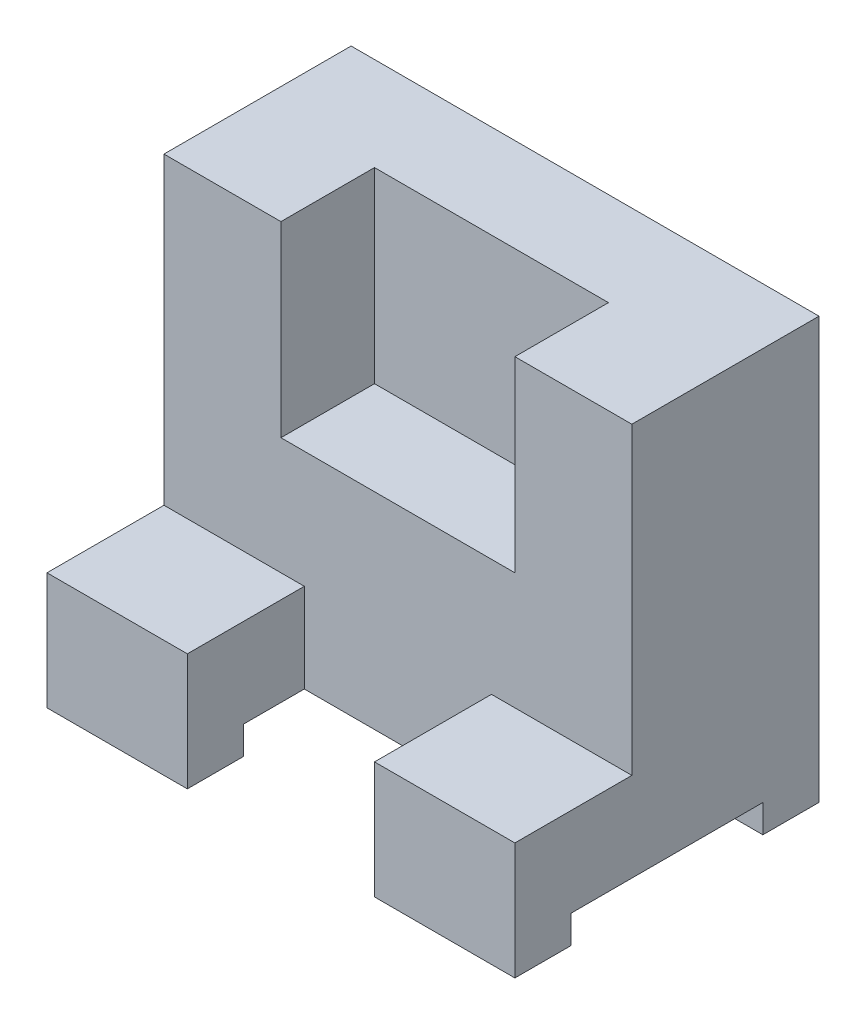
SolidWorks part; units mm, degrees
ref_plane "Front Plane" through (0, 0, 0) normal (0, 0, 1) x (1, 0, 0)
ref_plane "Top Plane" through (0, 0, 0) normal (0, 1, 0) x (1, 0, 0)
ref_plane "Right Plane" through (0, 0, 0) normal (1, 0, 0) x (0, 0, -1)
sketch "Sketch2" plane through (0, 0, 0) normal (0, 1, 0) x (1, 0, 0)
  line L1 (-50, 32.5) -> (50, 32.5)
  line L2 (-50, 32.5) -> (-50, -32.5)
  line L3 (-50, -32.5) -> (50, -32.5)
  line L4 (50, 32.5) -> (50, -32.5)
  line L5 (-50, 32.5) -> (50, -32.5) construction
  line L6 (-50, -32.5) -> (50, 32.5) construction
  point P0 (0, 0)
  dimension "D1" = 65
  dimension "D2" = 100
extrude "Boss-Extrude1" add sketch "Sketch2" along normal blind 25
sketch "Sketch3" plane through (0, 0, 0) normal (1, 0, 0) x (0, 0, -1)
  line L0 (32.5, 25) -> (32.5, 90)
  line L1 (32.5, 90) -> (-7.5, 90)
  line L2 (-7.5, 90) -> (-7.5, 25)
  line L3 (-32.5, 25) -> (32.5, 25) construction
  line L4 (-7.5, 25) -> (32.5, 25)
  dimension "D1" = 40
  dimension "D2" = 65
extrude "Boss-Extrude2" add sketch "Sketch3" along normal mid plane 100
sketch "Sketch4" plane through (0, 90, 0) normal (0, 1, 0) x (1, 0, 0)
  line L0 (-25, -7.5) -> (-25, 12.5)
  line L1 (50, -7.5) -> (-50, -7.5) construction
  line L2 (-25, 12.5) -> (25, 12.5)
  line L3 (25, 12.5) -> (25, -7.5)
  line L4 (25, -7.5) -> (-25, -7.5)
  line L5 (-50, 32.5) -> (-50, -7.5) construction
  line L6 (50, 32.5) -> (50, -7.5) construction
  dimension "D1" = 50
  dimension "D2" = 25
  dimension "D3" = 25
  dimension "D4" = 20
extrude "Cut-Extrude1" cut sketch "Sketch4" against normal blind 40
sketch "Sketch5" plane through (50, 0, 0) normal (1, 0, 0) x (0, 0, -1)
  line L0 (-20.5, 0) -> (-20.5, 5.9851)
  line L1 (-32.5, 0) -> (32.5, 0) construction
  line L2 (-20.5, 5.9851) -> (20.5, 5.9851)
  line L3 (20.5, 5.9851) -> (20.5, 0)
  line L4 (20.5, 0) -> (-20.5, 0)
  line L5 (-32.5, 25) -> (-32.5, 0) construction
  line L6 (32.5, 90) -> (32.5, 0) construction
  dimension "D1" = 12
  dimension "D2" = 12
  dimension "D3" = 41
extrude "Cut-Extrude2" cut sketch "Sketch5" against normal through all both and the other way through all
sketch "Sketch6" plane through (0, 0, 32.5) normal (0, 0, 1) x (1, 0, 0)
  line L0 (-20, 0) -> (-20, 25)
  line L1 (-50, 0) -> (50, 0) construction
  line L2 (-20, 25) -> (20, 25)
  line L3 (20, 25) -> (20, 0)
  line L4 (20, 0) -> (-20, 0)
  line L5 (-50, 25) -> (-50, 0) construction
  line L6 (50, 25) -> (50, 0) construction
  dimension "D1" = 30
  dimension "D2" = 30
  dimension "D3" = 25
extrude "Cut-Extrude4" cut sketch "Sketch6" against normal up to surface (25 mm away)
